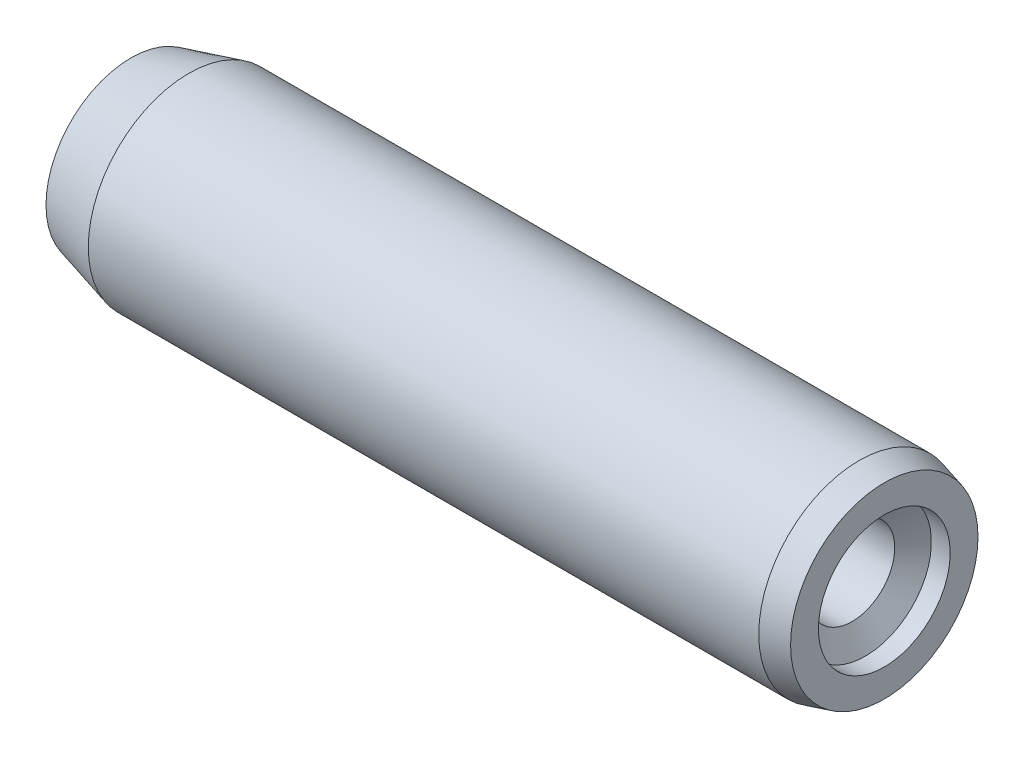
SolidWorks part; units mm, degrees
revolve "Body" add sketch "BodySke" angle 360 about L0
sketch "BodySke" plane through (0, 0, 0) normal (0, 0, 1) x (1, 0, 0)
  line L0 (0, 0) -> (66, 0) construction
  line L1 (0, 0) -> (40, 0) construction
  line L2 (4.6, 8) -> (58, 8)
  line L3 (58, 8) -> (60, 7.4641)
  line L4 (0, 0) -> (33.5917, 0)
  line L5 (60, 7.4641) -> (60, 5.25)
  line L6 (60, 5.25) -> (58.5, 5.25)
  line L7 (58.5, 5.25) -> (57.4319, 3.4)
  line L8 (57.4319, 3.4) -> (35, 3.4)
  line L9 (35, 3.4) -> (33.5917, 0)
  line L10 (57.25, 7) -> (57.25, 3) construction
  line L11 (44, 16) -> (44, 0) construction
  line L12 (4.6, 8) -> (0, 6.7674)
  line L13 (0, 0) -> (0, 6.7674)
  dimension "D1" = 75
  dimension "Head_ch_len" = 2
  dimension "Cbore_dia" = 10.5
  dimension "Cbore_dep" = 1.5
  dimension "Tapdrill_dia" = 6.8
  dimension "Tapdrill_dep" = 25
  dimension "D3" = 67.5
  dimension "Length" = 60
  dimension "D4" = 30
  dimension "Advance" = 1.25
  dimension "Thread_dep" = 16
  dimension "Diameter" = 16
  dimension "D2" = 165
  dimension "Tip_ch_len" = 4.6
cosmetic thread "ThreadCosmetic" [suppressed] parameters "Depth"=14.5, "Thread_major"=8
ref_plane "Plane1" through (0, 0, 0) normal (0, 0, 1) x (1, 0, 0)
ref_plane "Plane2" through (0, 0, 0) normal (0, 1, 0) x (1, 0, 0)
ref_plane "Plane3" through (0, 0, 0) normal (1, 0, 0) x (0, 0, -1)
sketch "ThdSchSke" plane through (0, 0, 0) normal (0, 0, 1) x (1, 0, 0)
  line L0 (57.7783, 4) -> (58.2618, 3.3095)
  line L2 (57.7783, 4) -> (57.2948, 3.3095)
  line L3 (57.2948, 3.3095) -> (58.2618, 3.3095)
  line L4 (57.7783, 5.8566) -> (57.7783, 1.7596) construction
  line L5 (27, 0) -> (36, 0) construction
  line L6 (0, 0) -> (66, 0) construction
  line L7 (60, -7.4641) -> (60, 7.4641) construction
  dimension "D1" = 70
revolve "ThreadSchematic" [suppressed] cut sketch "ThdSchSke" angle 360 about L5
pattern_linear "ThdSchPat" [suppressed]
equation "' \"Diameter@BodySke\" = 16"
equation "' \"Head_ch_len@BodySke\" = 2"
equation "' \"Tip_ch_len@BodySke\" = 4.6"
equation "' \"Thread_major@ThreadCosmetic\"  = 8"
equation "' \"Thread_major@ThreadCosmetic\" = 8"
equation "' \"Advance@BodySke\" = 1.25"
equation "' \"Cbore_dia@BodySke\" = 10.5"
equation "' \"Thread_dep@BodySke\"  = 16"
equation "' \"Thread_dep@BodySke\" = 16"
equation "' \"Tapdrill_dep@BodySke\" = 25"
equation "' \"Cbore_dep@BodySke\" = 1.5"
equation "' \"Tapdrill_dia@BodySke\" = 6.8"
equation "' \"Thread_minor@ThdSchSke\" = 6.619"
equation "'  \"Length@BodySke\" = 60"
equation "' \"Diameter@BodySke\" = 30"
equation "' \"Head_ch_len@BodySke\" = 4"
equation "' \"Tip_ch_len@BodySke\" = 7"
equation "' \"Thread_major@ThreadCosmetic\"  = 20"
equation "' \"Thread_major@ThreadCosmetic\" = 20"
equation "' \"Advance@BodySke\" = 2.5"
equation "' \"Cbore_dia@BodySke\" = 21"
equation "' \"Thread_dep@BodySke\"  = 30"
equation "' \"Thread_dep@BodySke\" = 30"
equation "' \"Tapdrill_dep@BodySke\" = 40"
equation "' \"Cbore_dep@BodySke\" = 2"
equation "' \"Tapdrill_dia@BodySke\" = 17.5"
equation "' \"Thread_minor@ThdSchSke\" = 17.252"
equation "\"Depth@ThreadCosmetic\" = \"Thread_dep@BodySke\"  -  \"Cbore_dep@BodySke\""
equation "\"Thread_nominal@ThdSchSke\" = \"Thread_major@ThreadCosmetic\""
equation "\"Inset@ThdSchSke\" = \"Cbore_dep@BodySke\" + (\"Cbore_dia@BodySke\" - \"Thread_major@ThreadCosmetic\") / 2 * tan(30 * 0.0174533)"
equation "\"Num_threads@ThdSchPat\" = int(  ( \"Thread_dep@BodySke\"  - \"Inset@ThdSchSke\" ) / \"Advance@BodySke\" + 0.999 )  + 1"
equation "\"Advance@ThdSchPat\" = (  \"Thread_dep@BodySke\" - \"Inset@ThdSchSke\" ) /  (\"Num_threads@ThdSchPat\" - 1) 'relax it"
